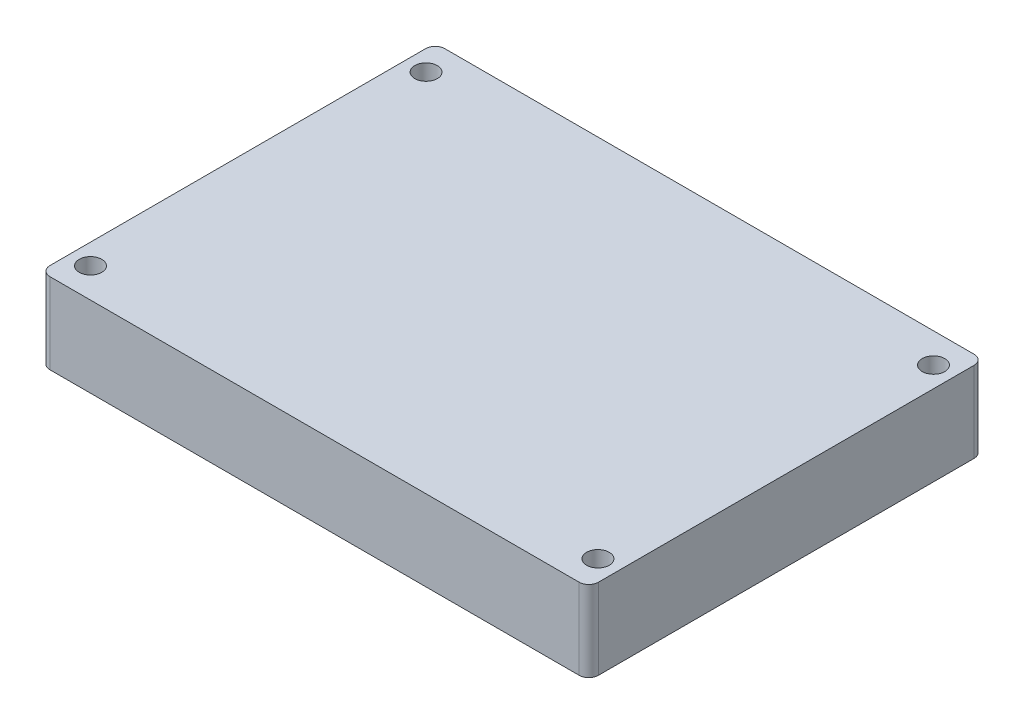
SolidWorks part; units mm, degrees
ref_plane "前视基准面" through (0, 0, 0) normal (0, 0, 1) x (1, 0, 0)
ref_plane "上视基准面" through (0, 0, 0) normal (0, 1, 0) x (1, 0, 0)
ref_plane "右视基准面" through (0, 0, 0) normal (1, 0, 0) x (0, 0, -1)
sketch "草图1" plane through (0, 0, 0) normal (0, 1, 0) x (1, 0, 0)
  line L1 (41, -30.6) -> (-41, -30.6)
  line L2 (42.5, -29.1) -> (42.5, 29.1)
  line L3 (41, 30.6) -> (-41, 30.6)
  line L4 (-42.5, -29.1) -> (-42.5, 29.1)
  line L5 (42.5, -30.6) -> (-42.5, 30.6) construction
  line L6 (42.5, 30.6) -> (-42.5, -30.6) construction
  line L7 (0, -30.6) -> (0, 30.6) construction
  line L8 (-42.5, 0) -> (42.5, 0) construction
  line L9 (27.1849, 0) -> (27.1849, 26.055) construction
  line L10 (0, 26.055) -> (39.47, 26.055) construction
  circle A4 centre (39.32, 26) radius 1.75
  arc A6 (41, -30.6) -> (42.5, -29.1) centre (41, -29.1) ccw
  arc A7 (42.5, 29.1) -> (41, 30.6) centre (41, 29.1) ccw
  arc A8 (-41, -30.6) -> (-42.5, -29.1) centre (-41, -29.1) cw
  arc A9 (-41, 30.6) -> (-42.5, 29.1) centre (-41, 29.1) ccw
  circle A10 centre (39.32, -26) radius 1.75
  circle A11 centre (-39.32, -26) radius 1.75
  circle A12 centre (-39.32, 26) radius 1.75
  point P0 (0, 0)
  dimension "D9" = 1.5
extrude "凸台-拉伸1" add sketch "草图1" along normal blind 12.5
